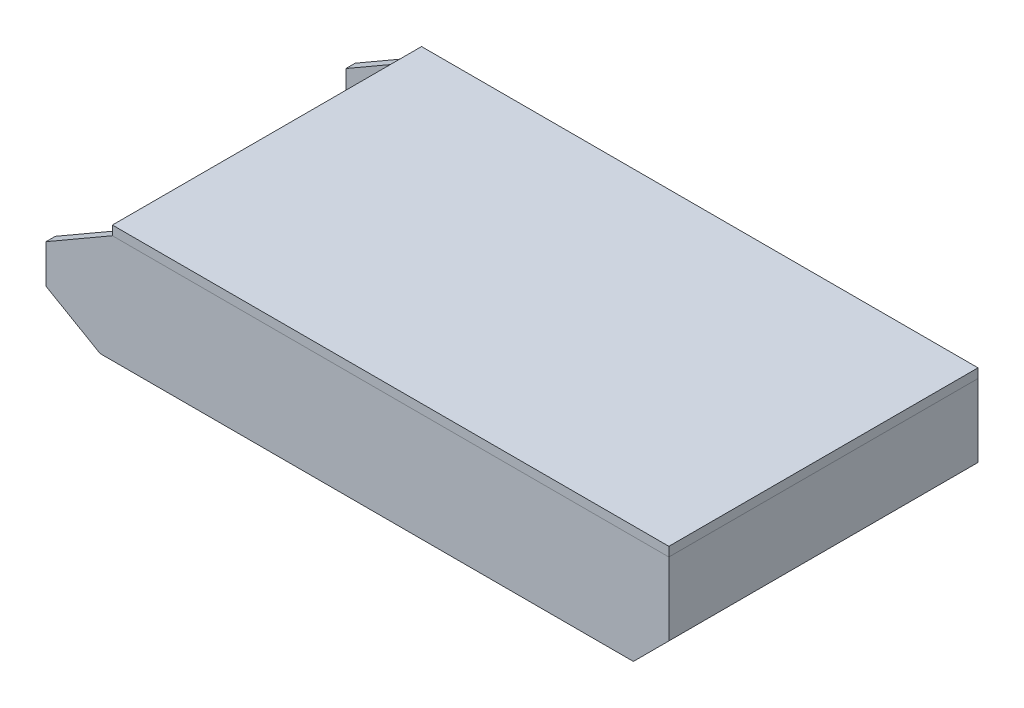
SolidWorks part; units mm, degrees
ref_plane "Front Plane" through (0, 0, 0) normal (0, 0, 1) x (1, 0, 0)
ref_plane "Top Plane" through (0, 0, 0) normal (0, 1, 0) x (1, 0, 0)
ref_plane "Right Plane" through (0, 0, 0) normal (1, 0, 0) x (0, 0, -1)
sketch "Sketch1" plane through (0, 0, 0) normal (0, 1, 0) x (1, 0, 0)
  line L0 (-180, 0) -> (180, 0) construction
  line L1 (-180, -100) -> (-180, 100) construction
  line L2 (-180, 100) -> (180, 100) construction
  line L3 (180, 100) -> (180, -100) construction
  line L4 (180, -100) -> (-180, -100) construction
  point P4 (0, 0)
  point P7 (-180, 0)
ref_plane "Back" through (180, 0, 0) normal (1, 0, 0) x (0, 0, -1)
ref_plane "Front" through (-180, 0, 0) normal (-1, 0, 0) x (0, 0, 1)
ref_plane "Left" through (0, 0, 100) normal (0, 0, 1) x (1, 0, 0)
ref_plane "Right" through (0, 0, -100) normal (0, 0, -1) x (-1, 0, 0)
sketch3d "3DSketch1"
  line L0 (-180, 0, 100) -> (-180, 300.6938, 100) construction
  line L1 (-180, 0, -100) -> (-180, 287.9975, -100) construction
  line L2 (180, 0, -100) -> (180, 282.9498, -100) construction
  line L3 (180, 0, 100) -> (180, 391.3038, 100) construction
  line L4 (-110, 0, -100) -> (-110, 0, 100) construction
  line L5 (-180, 0, -100) -> (180, 0, -100) construction
  line L6 (180, 0, 100) -> (-180, 0, 100) construction
  line L7 (157.0424, 0, 100) -> (157.0424, 0, -100) construction
  dimension "D1" = 110
  dimension "D2" = 157.0424
ref_plane "FrontMainBody" through (-55, -55, 0) normal (-0.7071, -0.7071, 0) x (0, 0, 1)
sketch "Left Panel(Main)" plane through (0, 0, 100) normal (0, 0, 1) x (1, 0, 0)
  line L0 (157.0424, 0) -> (-187.9576, 0)
  line L2 (-180, -200000) -> (-180, 200300.6938) construction
  line L3 (-180, 70) -> (180, 70)
  line L4 (180, -200000) -> (180, 200391.3038) construction
  line L5 (180, 70) -> (180, 22.9576)
  line L6 (180, 22.9576) -> (157.0424, 0)
  line L7 (-180, 70) -> (-222.9576, 45.1984)
  line L8 (-222.9576, 45.1984) -> (-222.9576, 20.2073)
  line L9 (-222.9576, 20.2073) -> (-187.9576, 0)
  line L10 (-180, 70) -> (-110, 0) construction
  dimension "D2" = 150
  dimension "D3" = 150
  dimension "D4" = 45
  dimension "D5" = 135
  dimension "D6" = 345
  dimension "D7" = 70
  dimension "D1" = 35
  dimension "D8" = 157.0424
sketch "Right Panel" plane through (0, 0, -100) normal (0, 0, -1) x (-1, 0, 0)
  line L0 (-180, 70) -> (180, 70)
  line L1 (180, 70) -> (222.9576, 45.1984)
  line L2 (222.9576, 45.1984) -> (222.9576, 20.2073)
  line L3 (222.9576, 20.2073) -> (187.9576, 0)
  line L4 (187.9576, 0) -> (-157.0424, 0)
  line L5 (-157.0424, 0) -> (-180, 22.9576)
  line L6 (-180, 22.9576) -> (-180, 70)
sketch3d "3DSketch4"
  line L0 (157.0424, 0, 100) -> (180, 22.9576, 100)
  line L1 (180, 22.9576, 100) -> (180, 70, 100)
  line L2 (180, 70, 100) -> (-180, 70, 100)
  line L3 (-180, 70, 100) -> (-222.9576, 45.1984, 100)
  line L4 (-222.9576, 45.1984, 100) -> (-222.9576, 20.2073, 100)
  line L5 (-222.9576, 20.2073, 100) -> (-187.9576, 0, 100)
  line L6 (-187.9576, 0, 100) -> (157.0424, 0, 100)
  line L7 (-187.9576, 0, -100) -> (157.0424, 0, -100)
  line L8 (-222.9576, 20.2073, -100) -> (-187.9576, 0, -100)
  line L9 (-222.9576, 45.1984, -100) -> (-222.9576, 20.2073, -100)
  line L10 (-180, 70, -100) -> (-222.9576, 45.1984, -100)
  line L11 (180, 70, -100) -> (-180, 70, -100)
  line L12 (180, 22.9576, -100) -> (180, 70, -100)
  line L13 (157.0424, 0, -100) -> (180, 22.9576, -100)
sketch "Sketch7" plane through (180, 0, 0) normal (1, 0, 0) x (0, 0, -1)
  line L0 (-94, 22.9576) -> (94, 22.9576)
  line L1 (-94, 22.9576) -> (-94, 70)
  line L2 (-94, 70) -> (94, 70)
  line L3 (94, 22.9576) -> (94, 70)
  dimension "D1" = 188
  dimension "D2" = 6
ref_plane "Plane2" through (78.5212, -78.5212, 0) normal (-0.7071, 0.7071, 0) x (0, 0, 1)
sketch "Sketch8" plane through (78.5212, -78.5212, 0) normal (-0.7071, 0.7071, 0) x (0, 0, 1)
  line L0 (-94, 143.5127) -> (-94, 111.0457)
  line L1 (-94, 111.0457) -> (94, 111.0457)
  line L2 (94, 111.0457) -> (94, 143.5127)
  line L3 (-94, 143.5127) -> (94, 143.5127)
  line L8 (100, 111.0457) -> (-100, 111.0457) construction
sketch "Sketch9" plane through (0, 0, 0) normal (0, 1, 0) x (1, 0, 0)
  line L0 (-110, -94) -> (151.0424, -94)
  line L1 (-110, 100) -> (-110, -100) construction
  line L3 (151.0424, -94) -> (151.0424, 94)
  line L4 (151.0424, 94) -> (-110, 94)
  line L5 (-110, 94) -> (-110, -94)
  line L6 (157.0424, -100) -> (-187.9576, -100) construction
  line L7 (-180, 100) -> (180, 100) construction
  dimension "D1" = 6
  dimension "D2" = 6
  dimension "D3" = 261.0424
extrude "Boss-Extrude2" add sketch "Right Panel" against normal blind 6
extrude "Boss-Extrude3" add sketch "Left Panel(Main)" against normal blind 6 separate body
sketch "Sketch12" plane through (0, 0, -94) normal (0, 0, 1) x (1, 0, 0)
  line L1 (-110, 8.4853) -> (-171.5147, 70)
  line L2 (-180, 70) -> (180, 70) construction
  line L3 (-171.5147, 70) -> (-180, 70)
  line L4 (-180, 70) -> (-110, 0)
  line L5 (-110, 0) -> (-110, 8.4853)
  line L6 (180, 70) -> (180, 22.9576) construction
  line L7 (-180, 70) -> (180, 70) construction
  dimension "D1" = 6
extrude "Boss-Extrude4" add sketch "Sketch12" along normal up to surface (188 mm away) separate body up to face at (-42.4044, 32.6233, 94)
sketch "Sketch13" plane through (0, 0, -94) normal (0, 0, 1) x (1, 0, 0)
  line L0 (180, 70) -> (174, 70)
  line L1 (-180, 70) -> (180, 70) construction
  line L2 (180, 70) -> (180, 22.9576)
  line L3 (180, 22.9576) -> (174, 22.9576)
  line L4 (174, 22.9576) -> (174, 70)
  dimension "D1" = 6
extrude "Boss-Extrude5" add sketch "Sketch13" along normal up to surface (188 mm away) separate body up to face at (-42.4044, 32.6233, 94)
sketch "Sketch14" plane through (0, 0, -94) normal (0, 0, 1) x (1, 0, 0)
  line L0 (180, 22.9576) -> (163.0424, 6)
  line L1 (163.0424, 6) -> (154.5571, 6)
  line L2 (154.5571, 6) -> (171.5147, 22.9576)
  line L3 (171.5147, 22.9576) -> (180, 22.9576)
  line L4 (157.0424, 0) -> (-187.9576, 0) construction
  line L5 (180, 22.9576) -> (157.0424, 0) construction
  line L6 (157.0424, 0) -> (180, 22.9576) construction
  dimension "D1" = 6
  dimension "D2" = 6
other "AlignGroup1"
sketch "Sketch15" plane through (0, 0, -94) normal (0, 0, 1) x (1, 0, 0)
  line L0 (-110, 0) -> (157.0424, 0)
  line L1 (-110, 0) -> (-110, 6)
  line L2 (-110, 0) -> (-110, 8.4853) construction
  line L3 (-110, 6) -> (163.0424, 6)
  line L4 (157.0424, 0) -> (163.0424, 6)
  line L5 (180, 70) -> (180, 22.9576) construction
  line L6 (-180, 70) -> (180, 70) construction
  dimension "D1" = 6
extrude "Boss-Extrude6" add sketch "Sketch15" along normal up to surface (188 mm away) up to face at (-42.4044, 32.6233, 94)
extrude "Boss-Extrude7" add sketch "Sketch14" along normal up to surface (188 mm away) up to face at (21.9213, 30.5738, 94)
sketch "Sketch16" plane through (0, 70, 0) normal (0, 1, 0) x (1, 0, 0)
  line L0 (-180, 100) -> (180, 100)
  line L1 (180, 100) -> (180, -100)
  line L2 (180, -100) -> (-180, -100)
  line L3 (-180, -100) -> (-180, 100)
extrude "Boss-Extrude8" add sketch "Sketch16" along normal blind 6 separate body
sketch "Sketch17" plane through (0, 0, -100) normal (0, 0, -1) x (-1, 0, 0)
  line L3 (-174, 70) -> (-174, 25.4429) construction
  line L4 (-174, 25.4429) -> (-154.5571, 6) construction
  line L5 (-154.5571, 6) -> (107.5147, 6) construction
  line L8 (-180, 70) -> (180, 70) construction
  line L9 (171.5147, 70) -> (107.5147, 6) construction
  line L10 (-180, 0) -> (180, 0) construction
  line L11 (171.5147, 70) -> (180, 70) construction
  line L12 (180, 70) -> (116, 6) construction
  line L13 (116, 6) -> (107.5147, 6) construction
  line L14 (-0.9143, 7.3253) -> (6.0718, 19.4256)
  line L15 (19.9282, 11.4256) -> (-12.0718, -44)
  line L20 (-70.9143, 7.3253) -> (-63.9282, 19.4256)
  line L21 (-50.0718, 11.4256) -> (-82.0718, -44)
  line L22 (-95.9282, -36) -> (-88.9421, -23.8997)
  line L23 (-89, -40) -> (-57, 15.4256) construction
  line L24 (-73, -12.2872) -> (-84.2583, -5.7872) construction
  line L25 (-25.9282, -36) -> (-18.9421, -23.8997)
  line L26 (-19, -40) -> (13, 15.4256) construction
  line L27 (-3, -12.2872) -> (-14.2583, -5.7872) construction
  line L28 (69.0857, 7.3253) -> (76.0718, 19.4256)
  line L29 (89.9282, 11.4256) -> (57.9282, -44)
  line L30 (44.0718, -36) -> (51.0579, -23.8997)
  line L31 (51, -40) -> (83, 15.4256) construction
  line L32 (67, -12.2872) -> (55.7417, -5.7872) construction
  line L33 (139.0857, 7.3253) -> (146.0718, 19.4256)
  line L34 (159.9282, 11.4256) -> (127.9282, -44)
  line L35 (114.0718, -36) -> (121.0579, -23.8997)
  line L36 (121, -40) -> (153, 15.4256) construction
  line L37 (137, -12.2872) -> (125.7417, -5.7872) construction
  circle A0 centre (-149, 35.7982) radius 25
  circle A1 centre (-89, -40) radius 20
  circle A2 centre (-19, -40) radius 20
  circle A3 centre (51, -40) radius 20
  circle A4 centre (121, -40) radius 20
  circle A5 centre (211, 35.7982) radius 20
  arc A10 (-12.352, -3.914) -> (-0.9143, 7.3253) centre (-26.8951, 22.3253) ccw
  arc A17 (-63.9282, 19.4256) -> (-50.0718, 11.4256) centre (-57, 15.4256) cw
  arc A18 (-95.9282, -36) -> (-82.0718, -44) centre (-89, -40) ccw
  circle A19 centre (-89, -40) radius 2.5
  circle A20 centre (-57, 15.4256) radius 2.5
  arc A21 (-82.352, -3.914) -> (-84.9274, -8.3747) centre (-79.9282, -8.2872) ccw
  arc A22 (-82.352, -3.914) -> (-70.9143, 7.3253) centre (-96.8951, 22.3253) ccw
  arc A23 (-84.9274, -8.3747) -> (-88.9421, -23.8997) centre (-114.9228, -8.8997) cw
  circle A24 centre (-81.6603, -7.2872) radius 1.5
  arc A25 (6.0718, 19.4256) -> (19.9282, 11.4256) centre (13, 15.4256) cw
  arc A26 (-25.9282, -36) -> (-12.0718, -44) centre (-19, -40) ccw
  arc A27 (-14.9274, -8.3747) -> (-18.9421, -23.8997) centre (-44.9228, -8.8997) cw
  arc A28 (-12.352, -3.914) -> (-14.9274, -8.3747) centre (-9.9282, -8.2872) ccw
  circle A29 centre (-11.6603, -7.2872) radius 1.5
  circle A30 centre (13, 15.4256) radius 2.5
  circle A31 centre (-19, -40) radius 2.5
  arc A32 (57.648, -3.914) -> (69.0857, 7.3253) centre (43.1049, 22.3253) ccw
  arc A33 (76.0718, 19.4256) -> (89.9282, 11.4256) centre (83, 15.4256) cw
  arc A34 (44.0718, -36) -> (57.9282, -44) centre (51, -40) ccw
  arc A35 (55.0726, -8.3747) -> (51.0579, -23.8997) centre (25.0772, -8.8997) cw
  arc A36 (57.648, -3.914) -> (55.0726, -8.3747) centre (60.0718, -8.2872) ccw
  circle A37 centre (58.3397, -7.2872) radius 1.5
  circle A38 centre (83, 15.4256) radius 2.5
  circle A39 centre (51, -40) radius 2.5
  arc A40 (127.648, -3.914) -> (139.0857, 7.3253) centre (113.1049, 22.3253) ccw
  arc A41 (146.0718, 19.4256) -> (159.9282, 11.4256) centre (153, 15.4256) cw
  arc A42 (114.0718, -36) -> (127.9282, -44) centre (121, -40) ccw
  arc A43 (125.0726, -8.3747) -> (121.0579, -23.8997) centre (95.0772, -8.8997) cw
  arc A44 (127.648, -3.914) -> (125.0726, -8.3747) centre (130.0718, -8.2872) ccw
  circle A45 centre (128.3397, -7.2872) radius 1.5
  circle A46 centre (153, 15.4256) radius 2.5
  circle A47 centre (121, -40) radius 2.5
  point P39 (-93, -46.9282)
  point P41 (-53, 22.3538)
  point P44 (-77.4282, -3.9571)
  point P51 (-84.2583, -5.7872)
  dimension "D2" = 50
  dimension "D1" = 40
  dimension "D6" = 40
  dimension "D15" = 60
  dimension "D16" = 80
  dimension "D17" = 30
  dimension "D18" = 3
  dimension "D20" = 8
  dimension "D23" = 5
  dimension "D24" = 5
  dimension "D25" = 10
  dimension "D3" = 60
  dimension "D4" = 60
  dimension "D7" = 90
  dimension "D8" = 4
  dimension "D19" = 3
  dimension "D5" = 4
equation "\"FrontAngle\"= 150deg"
equation "\"D2@Left Panel(Main)\" = \"FrontAngle\""
equation "\"D3@Left Panel(Main)\" = \"FrontAngle\""
